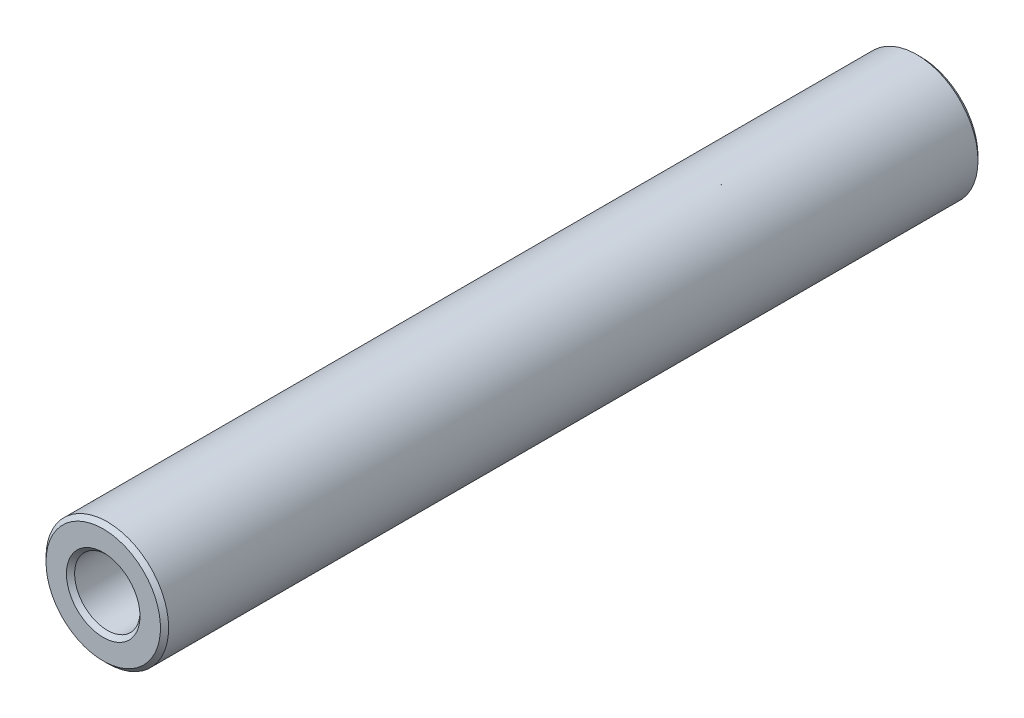
SolidWorks part; units mm, degrees
material "KS26"
ref_plane "正面" through (0, 0, 0) normal (0, 0, 1) x (1, 0, 0)
ref_plane "平面" through (0, 0, 0) normal (0, 1, 0) x (1, 0, 0)
ref_plane "右側面" through (0, 0, 0) normal (1, 0, 0) x (0, 0, -1)
sketch "ｽｹｯﾁ1" plane through (0, 0, 0) normal (1, 0, 0) x (0, 0, -1)
  line L0 (-7.1281, 0) -> (7.8719, 0) construction
  line L1 (0, 1.6) -> (0, 0) construction
  line L2 (-20, 3) -> (20, 3)
  line L3 (-20, 3) -> (-20, 1.6)
  line L4 (-20, 1.6) -> (20, 1.6)
  line L5 (20, 3) -> (20, 1.6)
  dimension "D1" = 40
  dimension "D2" = 6
  dimension "D3" = 3.2
revolve "回転1" add sketch "ｽｹｯﾁ1" angle 360 about L0
chamfer "面取り1" distance 0.2 angle 45 4 edges at (1.6, 0, 20) (1.6, 0, -20) (3, 0, -20) (3, 0, 20)
